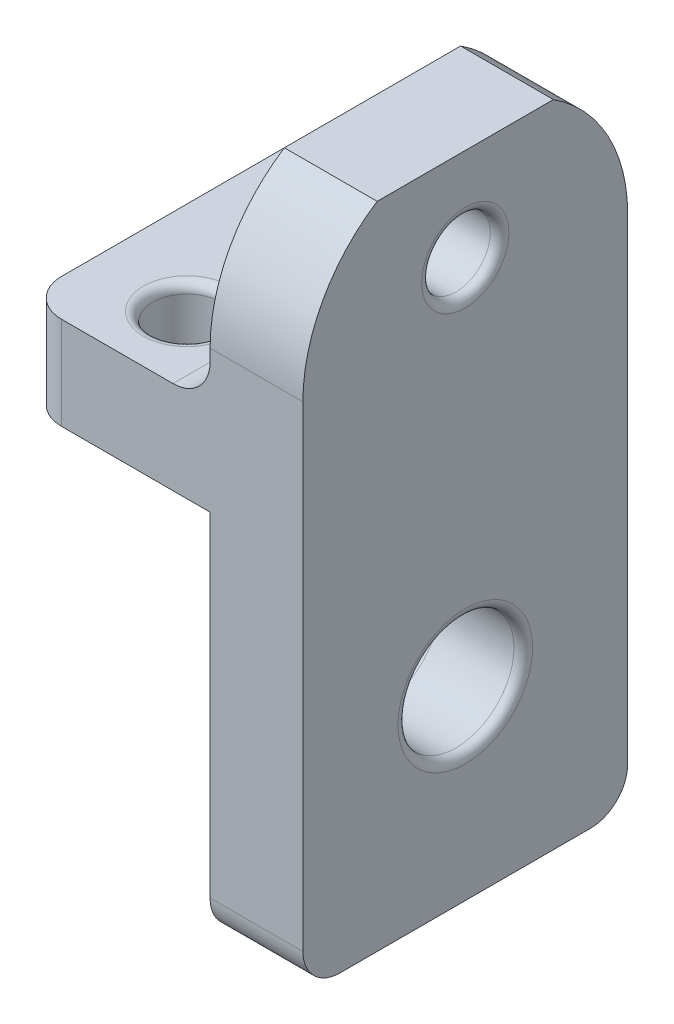
SolidWorks part; units mm, degrees
ref_plane "Front Plane" through (0, 0, 0) normal (0, 0, 1) x (1, 0, 0)
ref_plane "Top Plane" through (0, 0, 0) normal (0, 1, 0) x (1, 0, 0)
ref_plane "Right Plane" through (0, 0, 0) normal (1, 0, 0) x (0, 0, -1)
sketch "Sketch1" plane through (0, 0, 0) normal (0, 0, 1) x (1, 0, 0)
  line L0 (0, 0) -> (-12.7, 0)
  line L1 (-12.7, 0) -> (-12.7, 6.35)
  line L2 (-12.7, 6.35) -> (0, 6.35)
  line L3 (0, 6.35) -> (0, 19.05)
  line L4 (0, 19.05) -> (6.35, 19.05)
  line L5 (6.35, 19.05) -> (6.35, -25.4)
  line L6 (6.35, -25.4) -> (0, -25.4)
  line L7 (0, -25.4) -> (0, 0)
  line L8 (3.175, 19.05) -> (3.175, -25.4) construction
  point P11 (3.175, -12.7)
  point P12 (3.175, 12.7)
  dimension "D1" = 12.7
  dimension "D2" = 6.35
  dimension "D3" = 6.35
  dimension "D4" = 44.45
  dimension "D5" = 25.4
  dimension "D6" = 6.35
  dimension "D7" = 25.4
extrude "Boss-Extrude1" add sketch "Sketch1" along normal mid plane 22.225
sketch "Sketch2" plane through (0, 6.35, 0) normal (0, 1, 0) x (1, 0, 0)
  line L0 (-6.35, 11.1125) -> (-6.35, -11.1125) construction
  line L1 (0, 11.1125) -> (-12.7, 11.1125) construction
  line L2 (0, -11.1125) -> (-12.7, -11.1125) construction
  circle A0 centre (-6.35, 6.35) radius 2.3368
  circle A1 centre (-6.35, -6.35) radius 2.3368
  point P6 (-6.35, 6.35)
  point P7 (-6.35, -6.35)
  point P8 (-6.35, 0)
  dimension "D3" = 4.6736
  dimension "D1" = 12.7
  dimension "D2" = 6.35
extrude "Cut-Extrude1" cut sketch "Sketch2" against normal through all both and the other way through all
sketch "Sketch3" plane through (6.35, 0, 0) normal (1, 0, 0) x (0, 0, -1)
  circle A0 centre (0, 12.7) radius 2.3495
  circle A1 centre (0, -12.7) radius 3.9688
  point P3 (0, -12.7)
  dimension "D1" = 4.699
  dimension "D2" = 7.9375
extrude "Cut-Extrude2" cut sketch "Sketch3" against normal through all both and the other way through all
fillet "Fillet1" radius 2.54 6 edges at (-12.7, 3.175, -11.1125) (-12.7, 3.175, 11.1125) (3.175, -25.4, -11.1125) (3.175, -25.4, 11.1125) (3.175, 19.05, -11.1125) (3.175, 19.05, 11.1125)
fillet "Fillet2" radius 0.635 8 edges at (-6.35, 6.35, 4.0132) (-6.35, 0, 8.6868) (-6.35, 6.35, -8.6868) (-6.35, 0, -4.0132) (6.35, 10.3505, 0) (0, 12.7, -2.3495) (0, -12.7, -3.9688) (6.35, -16.6687, 0)
fillet "Fillet3" radius 2.54 1 edges at (0, 6.35, 0)
sketch "Sketch4" plane through (6.35, 0, 0) normal (1, 0, 0) x (0, 0, -1)
  line L0 (-17.4625, 9.7155) -> (-11.1125, 9.7155)
  line L1 (11.1125, 9.7155) -> (17.4625, 9.7155)
  line L2 (17.4625, 9.7155) -> (17.4625, 22.8708)
  line L3 (17.4625, 22.8708) -> (-17.4625, 22.8708)
  line L4 (-17.4625, 22.8708) -> (-17.4625, 9.7155)
  line L5 (-11.1125, -22.86) -> (-11.1125, 16.51) construction
  line L6 (11.1125, -22.86) -> (11.1125, 16.51) construction
  arc A0 (-11.1125, 9.7155) -> (11.1125, 9.7155) centre (0, 9.7155) cw
  circle A1 centre (0, 12.7) radius 2.9845 construction
  point P9 (-11.1125, 9.7155)
  point P12 (11.1125, 9.7155)
  dimension "D1" = 6.35
  dimension "D2" = 6.35
extrude "Cut-Extrude3" cut sketch "Sketch4" against normal through all both and the other way through all
